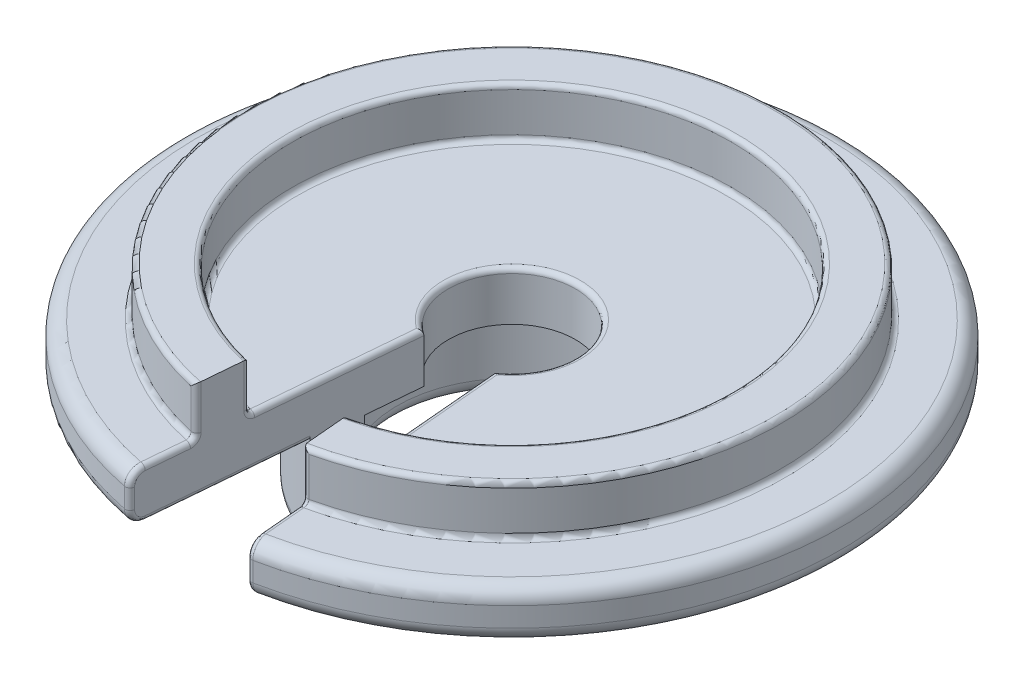
SolidWorks part; units mm, degrees
ref_plane "Front" through (0, 0, 0) normal (0, 0, 1) x (1, 0, 0)
ref_plane "Top" through (0, 0, 0) normal (0, 1, 0) x (1, 0, 0)
ref_plane "Right" through (0, 0, 0) normal (1, 0, 0) x (0, 0, -1)
sketch "Sketch1" plane through (0, 0, 0) normal (0, 0, 1) x (1, 0, 0)
  line L0 (0, -179.3251) -> (0, 8786.9305) construction
  line L1 (-1.651, 0) -> (-1.651, 1.27)
  line L2 (-1.651, 1.27) -> (-5.715, 1.27)
  line L3 (-5.715, 1.27) -> (-5.715, 2.54)
  line L4 (-5.715, 2.54) -> (-6.985, 2.54)
  line L5 (-6.985, 2.54) -> (-6.985, 1.27)
  line L6 (-6.985, 1.27) -> (-8.5725, 1.27)
  line L7 (-8.5725, 1.27) -> (-8.5725, 0)
  line L8 (-8.5725, 0) -> (-4.2545, 0)
  line L9 (-4.2545, 0) -> (-4.2545, -2.54)
  line L10 (-4.2545, -2.54) -> (-2.9845, -2.54)
  line L11 (-2.9845, -2.54) -> (-2.9845, 0)
  line L12 (-2.9845, 0) -> (-1.651, 0)
  dimension "D1" = 1.27
  dimension "D2" = 3.302
  dimension "D3" = 11.43
  dimension "D4" = 2.54
  dimension "D5" = 5.969
  dimension "D6" = 17.145
  dimension "D7" = 1.27
  dimension "D8" = 1.27
revolve "Revolve1" add sketch "Sketch1" angle 360 about L0
fillet "Fillet1" radius 0.381 4 edges at (2.9845, -2.54, 0) (4.2545, -2.54, 0) (8.5725, 0, 0) (8.5725, 1.27, 0)
sketch "Sketch2" plane through (0, 1.27, 0) normal (0, 1, 0) x (1, 0, 0)
  line L0 (-0.7937, 0) -> (0.7937, 0)
  line L1 (-1.5437, -8.5725) -> (1.5437, -8.5725)
  line L2 (-0.7937, 0) -> (-1.5437, -8.5725)
  line L3 (0.7937, 0) -> (1.5437, -8.5725)
  circle A1 centre (0, 0) radius 8.5725 construction
  point P5 (0, 0)
  point P8 (0, -8.5725)
  dimension "D1" = 1.5875
  dimension "D2" = 10
extrude "Cut-Extrude2" cut sketch "Sketch2" against normal through all both and the other way through all contours L2 L1 L3 L0
fillet "Fillet2" radius 0.127 21 edges at (-1.281, 1.905, 5.5696) (1.281, 1.905, 5.5696) (1.3926, 1.905, 6.8448) (-1.3926, 1.905, 6.8448) (1.3252, 0, 6.0744) (1.5244, 0.1439, 8.3518) (1.5317, 0.635, 8.4346) (1.522, 1.1572, 8.3241) (-1.3252, 0, 6.0744) (-1.5244, 0.1439, 8.3518) (-1.5317, 0.635, 8.4346) (-1.522, 1.1572, 8.3241) (0, 1.27, -1.651) (-1.0975, 1.27, 3.4722) (0, 1.27, -5.715) (1.0975, 1.27, 3.4722) (1.4455, 1.27, 7.449) (-1.4455, 1.27, 7.449) (0, 1.27, -6.985) (0, 2.54, -5.715) (0, 2.54, -6.985)
